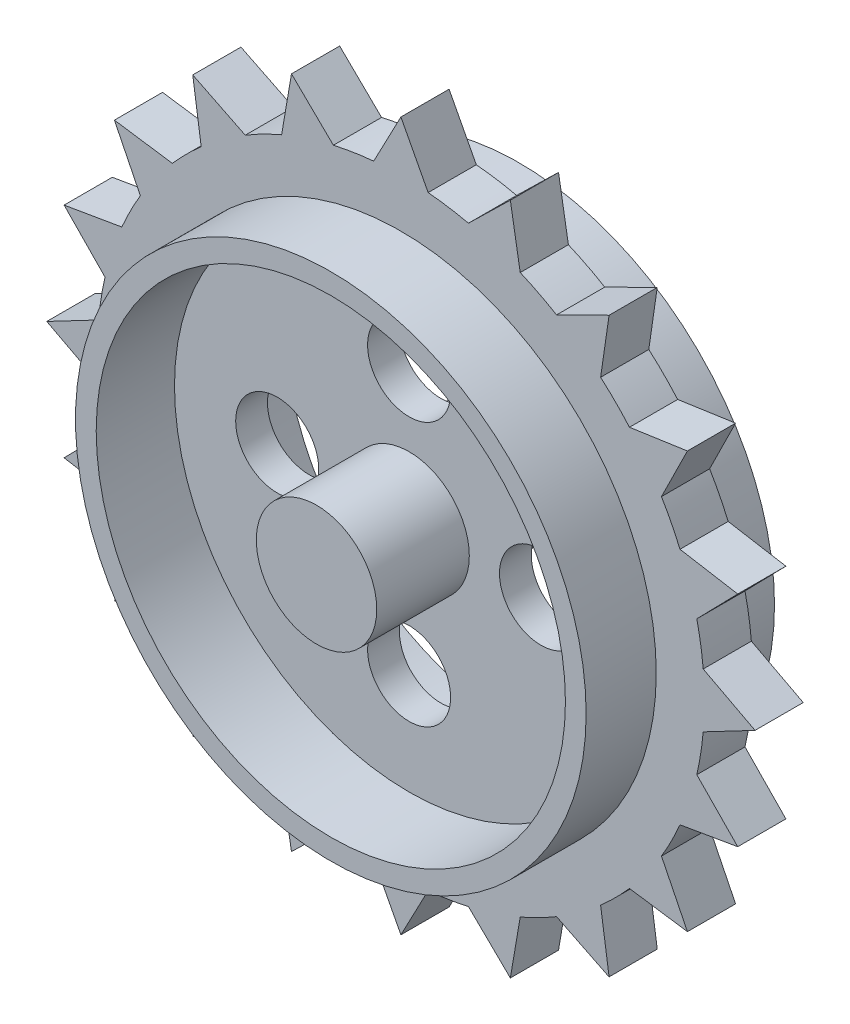
SolidWorks part; units mm, degrees
material "ABS"
ref_plane "Front Plane" through (0, 0, 0) normal (0, 0, 1) x (1, 0, 0)
ref_plane "Top Plane" through (0, 0, 0) normal (0, 1, 0) x (1, 0, 0)
ref_plane "Right Plane" through (0, 0, 0) normal (1, 0, 0) x (0, 0, -1)
sketch "Sketch1" plane through (0, 0, 0) normal (1, 0, 0) x (0, 0, -1)
  line L0 (0, 0) -> (-6.7605, 0) construction
  line L1 (4.9657, 13.462) -> (1.27, 13.462)
  line L2 (-4.9657, 13.462) -> (-4.9657, 12.3698)
  line L3 (4.9657, 13.462) -> (4.9657, 12.3698)
  line L4 (0, 0) -> (0, 16.002) construction
  line L5 (-1.27, 16.002) -> (1.27, 16.002)
  line L6 (-1.27, 16.002) -> (-1.27, 13.462)
  line L7 (1.27, 16.002) -> (1.27, 13.462)
  line L8 (-1.27, 13.462) -> (-4.9657, 13.462)
  line L9 (-4.9657, 12.3698) -> (-0.8382, 12.3698)
  line L10 (4.9657, 12.3698) -> (0.8382, 12.3698)
  line L11 (-0.8382, 12.3698) -> (-0.8382, 3.175)
  line L12 (-0.8382, 3.175) -> (-5.7198, 3.175)
  line L13 (-5.7198, 3.175) -> (-5.7198, 0)
  line L14 (-5.7198, 0) -> (0, 0)
  line L15 (0, 0) -> (14.6256, 0)
  line L16 (14.6256, 0) -> (14.6256, 3.175)
  line L17 (14.6256, 3.175) -> (0.8382, 3.175)
  line L18 (0.8382, 3.175) -> (0.8382, 12.3698)
  dimension "D1" = 26.924
  dimension "D2" = 1.0922
  dimension "D3" = 9.9314
  dimension "D4" = 32.004
  dimension "D5" = 2.54
  dimension "D6" = 4.1275
  dimension "D7" = 4.8816
  dimension "D8" = 6.35
  dimension "D9" = 20.3454
revolve "Revolve1" add sketch "Sketch1" angle 360 about L15
sketch "Sketch3" plane through (0, 0, -14.6256) normal (0, 0, -1) x (-1, 0, 0)
  line L1 (1.5398, 0) -> (0.7699, 1.3335)
  line L2 (0.7699, 1.3335) -> (-0.7699, 1.3335)
  line L3 (-0.7699, 1.3335) -> (-1.5398, 0)
  line L4 (-1.5398, 0) -> (-0.7699, -1.3335)
  line L5 (-0.7699, -1.3335) -> (0.7699, -1.3335)
  line L6 (0.7699, -1.3335) -> (1.5398, 0)
  circle A0 centre (0, 0) radius 1.3335 construction
  dimension "D1" = 2.667
extrude "Cut-Extrude2" cut sketch "Sketch3" against normal blind 17.78
sketch "Sketch4" plane through (0, 0, -0.8382) normal (0, 0, -1) x (-1, 0, 0)
  line L0 (0, 13.462) -> (0, 0) construction
  circle A0 centre (0, 6.9546) radius 2.1894
  circle A1 centre (6.9546, 0) radius 2.1894
  circle A2 centre (0, -6.9546) radius 2.1894
  circle A3 centre (-6.9546, 0) radius 2.1894
  circle A4 centre (0, 0) radius 13.462 construction
  circle A5 centre (0, 0) radius 13.462 construction
  point P12 (0, 0)
  dimension "D2" = 4.3789
  dimension "D3" = 4.318
  dimension "D1" = 4
extrude "Cut-Extrude3" cut sketch "Sketch4" against normal up to surface (1.6764 mm away) up to face at (3.175, 0, 0.8382)
sketch "Sketch5" plane through (0, 0, 1.27) normal (0, 0, 1) x (1, 0, 0)
  line L0 (0, 0) -> (18.6715, 0) construction
  line L1 (18.6715, 0) -> (15.9375, 1.4351)
  line L2 (18.6715, 0) -> (15.9375, -1.4351)
  line L3 (17.7576, -5.7698) -> (14.714, -6.2898)
  line L4 (17.7576, -5.7698) -> (15.601, -3.5601)
  line L5 (15.1055, -10.9748) -> (12.0502, -10.5289)
  line L6 (15.1055, -10.9748) -> (13.7373, -8.2068)
  line L7 (10.9748, -15.1055) -> (8.2068, -13.7373)
  line L8 (10.9748, -15.1055) -> (10.5289, -12.0502)
  line L9 (5.7698, -17.7576) -> (3.5601, -15.601)
  line L10 (5.7698, -17.7576) -> (6.2898, -14.714)
  line L11 (0, -18.6715) -> (-1.4351, -15.9375)
  line L12 (0, -18.6715) -> (1.4351, -15.9375)
  line L13 (-5.7698, -17.7576) -> (-6.2898, -14.714)
  line L14 (-5.7698, -17.7576) -> (-3.5601, -15.601)
  line L15 (-10.9748, -15.1055) -> (-10.5289, -12.0502)
  line L16 (-10.9748, -15.1055) -> (-8.2068, -13.7373)
  line L17 (-15.1055, -10.9748) -> (-13.7373, -8.2068)
  line L18 (-15.1055, -10.9748) -> (-12.0502, -10.5289)
  line L19 (-17.7576, -5.7698) -> (-15.601, -3.5601)
  line L20 (-17.7576, -5.7698) -> (-14.714, -6.2898)
  line L21 (-18.6715, 0) -> (-15.9375, 1.4351)
  line L22 (-18.6715, 0) -> (-15.9375, -1.4351)
  line L23 (-17.7576, 5.7698) -> (-14.714, 6.2898)
  line L24 (-17.7576, 5.7698) -> (-15.601, 3.5601)
  line L25 (-15.1055, 10.9748) -> (-12.0502, 10.5289)
  line L26 (-15.1055, 10.9748) -> (-13.7373, 8.2068)
  line L27 (-10.9748, 15.1055) -> (-8.2068, 13.7373)
  line L28 (-10.9748, 15.1055) -> (-10.5289, 12.0502)
  line L29 (-5.7698, 17.7576) -> (-3.5601, 15.601)
  line L30 (-5.7698, 17.7576) -> (-6.2898, 14.714)
  line L31 (0, 18.6715) -> (1.4351, 15.9375)
  line L32 (0, 18.6715) -> (-1.4351, 15.9375)
  line L33 (5.7698, 17.7576) -> (6.2898, 14.714)
  line L34 (5.7698, 17.7576) -> (3.5601, 15.601)
  line L35 (10.9748, 15.1055) -> (10.5289, 12.0502)
  line L36 (10.9748, 15.1055) -> (8.2068, 13.7373)
  line L37 (15.1055, 10.9748) -> (13.7373, 8.2068)
  line L38 (15.1055, 10.9748) -> (12.0502, 10.5289)
  line L39 (17.7576, 5.7698) -> (15.601, 3.5601)
  line L40 (17.7576, 5.7698) -> (14.714, 6.2898)
  circle A0 centre (0, 0) radius 16.002 construction
  circle A1 centre (0, 0) radius 16.002
  point P3 (16.002, 0)
  point P67 (0, 0)
  circle M44 centre (0, 0) radius 16.002
  dimension "D1" = 2.8702
  dimension "D2" = 2.6695
  dimension "D3" = 20
extrude "Boss-Extrude1" add sketch "Sketch5" against normal up to surface (2.54 mm away) contours L25 L26 M44 | L27 L28 M44 | L29 L30 M44 | L31 L32 M44 | L33 L34 M44 | L35 L36 M44 | L37 L38 M44 | L39 L40 M44 | L0 L2 M44 | A1 L0 L1 | L3 L4 M44 | L5 L6 M44 | L7 L8 M44 | L9 L10 M44 | L11 L12 M44 | L13 L14 M44 | L15 L16 M44 | L17 L18 M44 | L19 L20 M44 | L21 L22 M44 | L23 L24 M44 up to face at (16.002, 0, -1.27)
sketch "Sketch6" plane through (0, 0, -4.9657) normal (0, 0, -1) x (-1, 0, 0)
  circle A0 centre (0, 0) radius 12.3698
extrude "Cut-Extrude4" cut sketch "Sketch6" along normal through all
